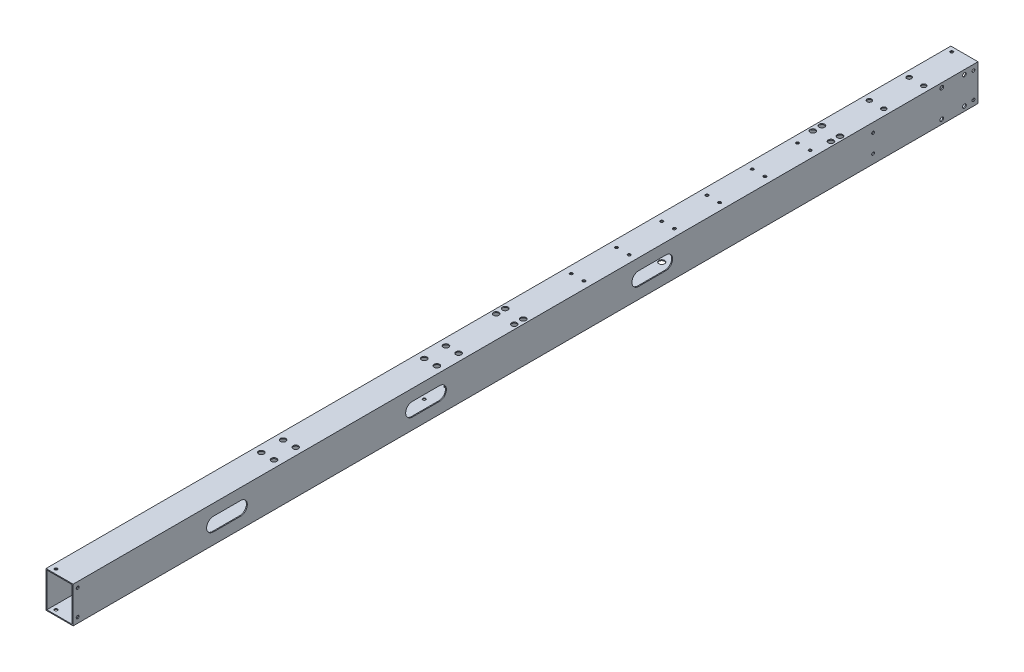
SolidWorks part; units mm, degrees
material "6061 合金"
ref_plane "Front" through (0, 0, 0) normal (0, 0, 1) x (1, 0, 0)
ref_plane "Top" through (0, 0, 0) normal (0, 1, 0) x (1, 0, 0)
ref_plane "Right" through (0, 0, 0) normal (1, 0, 0) x (0, 0, -1)
sketch "草图1" plane through (0, 0, 0) normal (0, 0, 1) x (1, 0, 0)
  line L1 (-15, -20) -> (15, -20)
  line L2 (-15, -20) -> (-15, 20)
  line L3 (-15, 20) -> (15, 20)
  line L4 (15, -20) -> (15, 20)
  line L5 (-15, -20) -> (15, 20) construction
  line L6 (-15, 20) -> (15, -20) construction
  line L7 (-14, -19) -> (14, -19)
  line L8 (-14, -19) -> (-14, 19)
  line L9 (-14, 19) -> (14, 19)
  line L10 (14, -19) -> (14, 19)
  line L11 (-14, -19) -> (14, 19) construction
  line L12 (-14, 19) -> (14, -19) construction
  point P0 (0, 0)
  point P5 (0, 0)
  dimension "D1" = 30
  dimension "D2" = 40
  dimension "D3" = 1
  dimension "D4" = 1
extrude "凸台-拉伸1" add sketch "草图1" along normal blind 1000
sketch "草图2" plane through (15, 0, 0) normal (1, 0, 0) x (0, 0, -1)
  line L0 (-1000, 20) -> (0, 20) construction
  line L1 (-1000, -20) -> (-1000, 20) construction
  line L2 (-1000, -20) -> (0, -20) construction
  line L3 (0, -20) -> (0, 20) construction
  circle A0 centre (-995, 14) radius 1.6
  circle A1 centre (-995, -14) radius 1.6
  circle A2 centre (-5, 14) radius 1.6
  circle A3 centre (-5, -14) radius 1.6
  dimension "D1" = 3.2
  dimension "D2" = 6
  dimension "D3" = 5
  dimension "D4" = 6
  dimension "D5" = 5
  dimension "D6" = 3.2
  dimension "D7" = 5
  dimension "D8" = 6
  dimension "D9" = 5
  dimension "D10" = 6
  dimension "D11" = 3.2
  dimension "D12" = 3.2
extrude "切除-拉伸1" cut sketch "草图2" against normal blind 10
sketch "草图3" plane through (0, 20, 0) normal (0, 1, 0) x (1, 0, 0)
  line L0 (15, -1000) -> (-15, -1000) construction
  line L1 (-15, -1000) -> (-15, 0) construction
  line L2 (15, 0) -> (-15, 0) construction
  circle A0 centre (-9, -995) radius 1.6
  circle A1 centre (-9, -5) radius 1.6
  dimension "D1" = 3.2
  dimension "D2" = 5
  dimension "D3" = 6
  dimension "D4" = 3.2
  dimension "D5" = 6
  dimension "D6" = 5
extrude "切除-拉伸2" cut sketch "草图3" against normal through all
sketch "草图5" plane through (0, -20, 0) normal (0, -1, 0) x (1, 0, 0)
  line L0 (-8, 97) -> (-8, 53) construction
  line L1 (-8, 53) -> (8, 53) construction
  line L2 (8, 53) -> (8, 97) construction
  line L3 (8, 97) -> (-8, 97) construction
  line L4 (-15, 0) -> (15, 0) construction
  line L5 (-15, 1000) -> (-15, 0) construction
  line L6 (15, 1000) -> (15, 0) construction
  circle A0 centre (-8, 53) radius 2.6
  circle A1 centre (8, 53) radius 2.6
  circle A2 centre (-8, 97) radius 2.6
  circle A3 centre (8, 97) radius 2.6
  dimension "D1" = 5.2
  dimension "D2" = 5.2
  dimension "D3" = 5.2
  dimension "D4" = 5.2
  dimension "D5" = 44
  dimension "D6" = 53
  dimension "D7" = 7
  dimension "D8" = 7
extrude "切除-拉伸3" cut sketch "草图5" against normal through all
sketch "草图6" plane through (15, 0, 0) normal (1, 0, 0) x (0, 0, -1)
  line L0 (-345, 0) -> (-375, 0) construction
  line L1 (-345, -7.5) -> (-375, -7.5)
  line L2 (-345, 7.5) -> (-375, 7.5)
  line L3 (0, 0) -> (-119.9993, 0) construction
  line L4 (0, -20) -> (0, 20) construction
  line L5 (-595, 0) -> (-625, 0) construction
  line L6 (-595, -7.5) -> (-625, -7.5)
  line L7 (-595, 7.5) -> (-625, 7.5)
  line L8 (-815, 0) -> (-845, 0) construction
  line L11 (-815, -7.5) -> (-845, -7.5)
  line L12 (-40, 15) -> (-15, 15) construction
  line L13 (-40, 15) -> (-40, -15) construction
  line L14 (-40, -15) -> (-15, -15) construction
  line L15 (-15, 15) -> (-15, -15) construction
  line L16 (-40, 15) -> (-15, -15) construction
  line L17 (-40, -15) -> (-15, 15) construction
  line L18 (-815, 7.5) -> (-845, 7.5)
  arc A0 (-345, -7.5) -> (-345, 7.5) centre (-345, 0) ccw
  arc A1 (-375, 7.5) -> (-375, -7.5) centre (-375, 0) ccw
  arc A2 (-595, -7.5) -> (-595, 7.5) centre (-595, 0) ccw
  arc A3 (-625, 7.5) -> (-625, -7.5) centre (-625, 0) ccw
  circle A6 centre (-40, 15) radius 2.05
  circle A7 centre (-15, 15) radius 2.05
  circle A8 centre (-15, -15) radius 2.05
  circle A9 centre (-40, -15) radius 2.05
  arc A10 (-815, -7.5) -> (-815, 7.5) centre (-815, 0) ccw
  arc A11 (-845, 7.5) -> (-845, -7.5) centre (-845, 0) ccw
  point P3 (-360, 0)
  point P10 (-610, 0)
  point P21 (-830, 0)
  point P26 (-27.5, 0)
  dimension "D7" = 4.1
  dimension "D1" = 30
  dimension "D2" = 15
  dimension "D3" = 345
  dimension "D5" = 25
  dimension "D6" = 15
  dimension "0" = 30
  dimension "D8" = 250
  dimension "D10" = 220
  dimension "D4" = 2
  dimension "D9" = 2
extrude "切除-拉伸4" cut sketch "草图6" against normal blind 1
sketch "草图7" plane through (-15, 0, 0) normal (-1, 0, 0) x (0, 0, 1)
  line L0 (0, 20) -> (0, -20) construction
  circle A0 centre (350, 0) radius 1.6
  circle A1 centre (370, 0) radius 1.6
  circle A2 centre (600, 0) radius 1.6
  circle A3 centre (620, 0) radius 1.6
  circle A4 centre (850, 0) radius 1.6
  circle A5 centre (870, 0) radius 1.6
  dimension "D1" = 3.2
  dimension "D2" = 350
  dimension "D3" = 2
  dimension "D4" = 3
extrude "切除-拉伸5" cut sketch "草图7" against normal blind 1
sketch "草图9" plane through (0, 20, 0) normal (0, 1, 0) x (1, 0, 0)
  circle A2 centre (-10, -507.5) radius 3
  circle A3 centre (-10, -507.5) radius 3
  circle A5 centre (-10, -497.5) radius 3
  circle A6 centre (-10, -497.5) radius 3
  circle A8 centre (10, -497.5) radius 3
  circle A9 centre (10, -497.5) radius 3
  circle A11 centre (10, -507.5) radius 3
  circle A12 centre (10, -507.5) radius 3
  circle A14 centre (-10, -147.5) radius 3
  circle A15 centre (-10, -147.5) radius 3
  circle A17 centre (-10, -157.5) radius 3
  circle A18 centre (-10, -157.5) radius 3
  circle A20 centre (10, -157.5) radius 3
  circle A21 centre (10, -157.5) radius 3
  circle A23 centre (10, -147.5) radius 3
  circle A24 centre (10, -147.5) radius 3
  dimension "D1" = 1.5
  dimension "D2" = 1.5
  dimension "D3" = 1.5
  dimension "D4" = 1.5
  dimension "D5" = 1.5
  dimension "D6" = 1.5
  dimension "D7" = 1.5
  dimension "D8" = 1.5
extrude "切除-拉伸9" cut sketch "草图9" against normal blind 1
sketch "草图11" plane through (0, 20, 0) normal (0, 1, 0) x (1, 0, 0)
  line L0 (-15, -1000) -> (-15, 0) construction
  line L1 (15, -1000) -> (15, 0) construction
  line L2 (-7, -177.5) -> (7, -177.5) construction
  line L3 (-7, -227.5) -> (7, -227.5) construction
  line L4 (-7, -277.5) -> (7, -277.5) construction
  line L5 (-7, -327.5) -> (7, -327.5) construction
  line L6 (-7, -377.5) -> (7, -377.5) construction
  line L7 (-7, -427.5) -> (7, -427.5) construction
  circle A0 centre (-7, -177.5) radius 1.6
  circle A1 centre (7, -177.5) radius 1.6
  circle A2 centre (10, -157.5) radius 3 construction
  circle A3 centre (-7, -227.5) radius 1.6
  circle A4 centre (7, -227.5) radius 1.6
  circle A5 centre (-7, -277.5) radius 1.6
  circle A6 centre (7, -277.5) radius 1.6
  circle A7 centre (-7, -327.5) radius 1.6
  circle A8 centre (7, -327.5) radius 1.6
  circle A9 centre (-7, -377.5) radius 1.6
  circle A10 centre (7, -377.5) radius 1.6
  circle A11 centre (-7, -427.5) radius 1.6
  circle A12 centre (7, -427.5) radius 1.6
  dimension "D1" = 3.2
  dimension "D2" = 8
  dimension "D3" = 8
  dimension "D6" = 3.2
  dimension "D4" = 20
  dimension "D5" = 6
extrude "切除-拉伸10" cut sketch "草图11" against normal through all
sketch "草图12" plane through (0, -20, 0) normal (0, -1, 0) x (1, 0, 0)
  circle A0 centre (-7, 227.5) radius 3.25
  circle A1 centre (7, 227.5) radius 3.25
  circle A2 centre (-7, 277.5) radius 3.25
  circle A3 centre (7, 277.5) radius 3.25
  circle A4 centre (-7, 327.5) radius 3.25
  circle A6 centre (-7, 177.5) radius 3.25
  circle A7 centre (7, 177.5) radius 3.25
  circle A8 centre (7, 327.5) radius 3.25
  circle A9 centre (-7, 377.5) radius 3.25
  circle A10 centre (7, 377.5) radius 3.25
  circle A11 centre (-7, 427.5) radius 3.25
  circle A12 centre (7, 427.5) radius 3.25
  dimension "D1" = 6.5
  dimension "D2" = 6.5
  dimension "D3" = 6
extrude "切除-拉伸11" cut sketch "草图12" against normal blind 1
sketch "草图16" plane through (0, 20, 0) normal (0, 1, 0) x (1, 0, 0)
  line L0 (0, -1000) -> (0, -516) construction
  line L1 (-7, -746) -> (7, -746) construction
  line L2 (-7, -746) -> (-7, -770) construction
  line L3 (-7, -770) -> (7, -770) construction
  line L4 (7, -746) -> (7, -770) construction
  line L5 (-7, -746) -> (7, -770) construction
  line L6 (-7, -770) -> (7, -746) construction
  line L7 (15, -1000) -> (-15, -1000) construction
  circle A0 centre (-7, -770) radius 3
  circle A1 centre (7, -770) radius 3
  circle A2 centre (-7, -590) radius 3
  circle A3 centre (-7, -590) radius 3
  circle A4 centre (-7, -746) radius 3
  circle A5 centre (7, -590) radius 3
  circle A6 centre (7, -590) radius 3
  circle A7 centre (7, -746) radius 3
  circle A8 centre (7, -566) radius 3
  circle A9 centre (7, -566) radius 3
  circle A11 centre (-7, -566) radius 3
  circle A12 centre (-7, -566) radius 3
  point P0 (0, -758)
  dimension "D7" = 6
  dimension "D5" = 14
  dimension "D6" = 24
  dimension "D8" = 180
  dimension "D1" = 1.5
  dimension "D2" = 1.5
  dimension "D3" = 1.5
  dimension "D4" = 1.5
extrude "切除-拉伸15" cut sketch "草图16" against normal blind 1
sketch "草图18" plane through (0, -20, 0) normal (0, -1, 0) x (1, 0, 0)
  circle A0 centre (-7, 746) radius 3 construction
  circle A1 centre (7, 746) radius 3 construction
  circle A2 centre (-7, 770) radius 3 construction
  circle A3 centre (7, 770) radius 3 construction
  circle A4 centre (-7, 746) radius 3 construction
  circle A5 centre (7, 746) radius 3 construction
  circle A6 centre (-7, 770) radius 3 construction
  circle A7 centre (7, 770) radius 3 construction
  circle A8 centre (-7, 770) radius 1.55
  circle A9 centre (7, 770) radius 1.55
  circle A10 centre (-7, 746) radius 1.55
  circle A11 centre (7, 746) radius 1.55
  dimension "D1" = 1.45
extrude "切除-拉伸16" cut sketch "草图18" against normal blind 10
sketch "草图21" plane through (0, -20, 0) normal (0, -1, 0) x (1, 0, 0)
  circle A0 centre (-10, 147.5) radius 1.6
  circle A1 centre (-10, 157.5) radius 1.6
  circle A2 centre (10, 147.5) radius 1.6
  circle A3 centre (10, 157.5) radius 1.6
  circle A4 centre (-10, 497.5) radius 1.6
  circle A5 centre (-10, 507.5) radius 1.6
  circle A6 centre (10, 497.5) radius 1.6
  circle A7 centre (10, 507.5) radius 1.6
  circle A8 centre (-7, 566) radius 1.6
  circle A9 centre (-7, 590) radius 1.6
  circle A10 centre (7, 566) radius 1.6
  circle A11 centre (7, 590) radius 1.6
  circle A12 centre (-7, 746) radius 1.6
  circle A13 centre (-7, 770) radius 1.6
  circle A14 centre (7, 746) radius 1.6
  circle A15 centre (7, 770) radius 1.6
  dimension "D1" = 3.2
extrude "切除-拉伸18" cut sketch "草图21" against normal through all
sketch "草图23" plane through (15, 0, 0) normal (1, 0, 0) x (0, 0, -1)
  line L0 (0, -20) -> (0, 20) construction
  line L1 (-1000, -20) -> (0, -20) construction
  circle A0 centre (-116, 10) radius 1.55
  circle A1 centre (-116, -10) radius 1.55
  dimension "D1" = 3.1
  dimension "D4" = 3.1
  dimension "D5" = 116
  dimension "D2" = 116
  dimension "D3" = 30
  dimension "D6" = 10
extrude "切除-拉伸19" cut sketch "草图23" against normal blind 30
